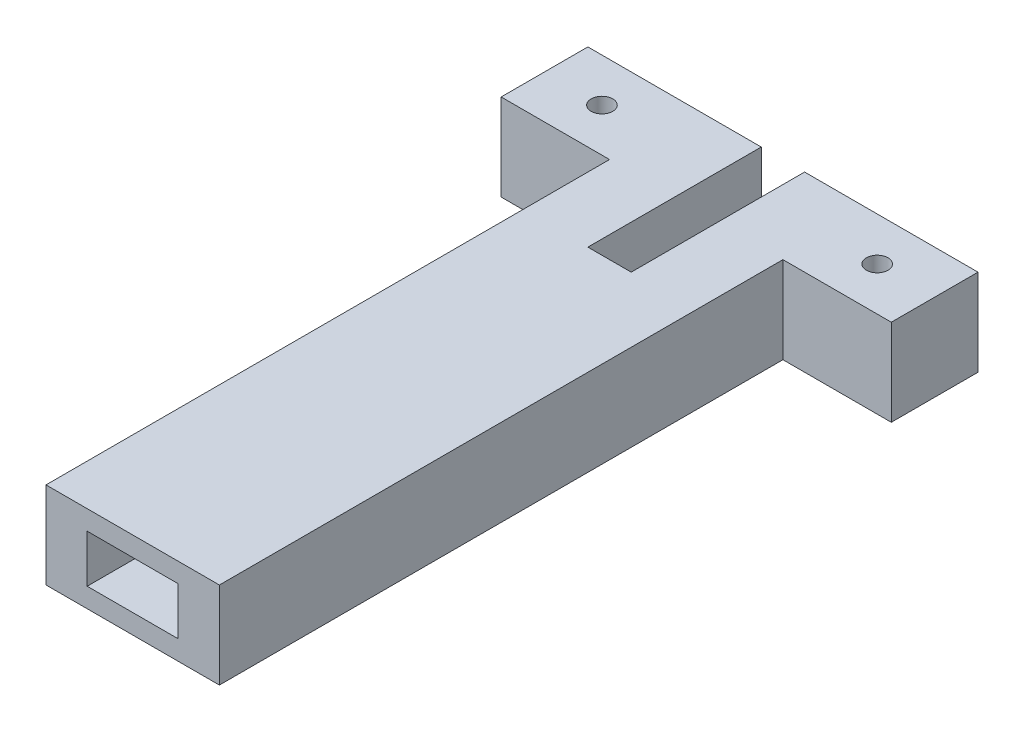
SolidWorks part; units mm, degrees
ref_plane "Front Plane" through (0, 0, 0) normal (0, 0, 1) x (1, 0, 0)
ref_plane "Top Plane" through (0, 0, 0) normal (0, 1, 0) x (1, 0, 0)
ref_plane "Right Plane" through (0, 0, 0) normal (1, 0, 0) x (0, 0, -1)
sketch "Sketch1" plane through (0, 0, 0) normal (0, 1, 0) x (1, 0, 0)
  line L0 (10, -5) -> (22.5, -5)
  line L1 (-22.5, -5) -> (-10, -5)
  line L2 (-22.5, -5) -> (-22.5, 5)
  line L3 (-22.5, 5) -> (-2.5, 5)
  line L4 (22.5, -5) -> (22.5, 5)
  line L5 (-22.5, -5) -> (22.5, 5) construction
  line L6 (-22.5, 5) -> (22.5, -5) construction
  line L7 (-10, -70) -> (10, -70)
  line L8 (-10, -70) -> (-10, -5)
  line L10 (10, -70) -> (10, -5)
  line L11 (-10, -70) -> (10, -5) construction
  line L12 (-10, -5) -> (10, -70) construction
  line L13 (2.5, 5) -> (22.5, 5)
  line L14 (-2.5, -15) -> (2.5, -15)
  line L15 (-2.5, -15) -> (-2.5, 5)
  line L17 (2.5, -15) -> (2.5, 5)
  line L18 (-2.5, -15) -> (2.5, 5) construction
  line L19 (-2.5, 5) -> (2.5, -15) construction
  circle A0 centre (-15.875, 0) radius 1.25
  circle A1 centre (15.875, 0) radius 1.25
  point P0 (0, 0)
  point P10 (0, -37.5)
  point P15 (0, -15)
  point P17 (0, -5)
  dimension "D2" = 15.875
  dimension "D3" = 31.75
  dimension "D4" = 2.5
  dimension "D5" = 2.5
  dimension "D1" = 45
  dimension "D6" = 65
  dimension "D7" = 20
  dimension "D8" = 10
  dimension "D9" = 5
  dimension "D10" = 20
extrude "Boss-Extrude1" add sketch "Sketch1" along normal blind 10
sketch "Sketch2" plane through (0, 0, 70) normal (0, 0, 1) x (1, 0, 0)
  line L0 (22.5, 10) -> (22.5, 0) construction
  line L1 (-5.25, 2.25) -> (5.25, 2.25)
  line L2 (-5.25, 2.25) -> (-5.25, 7.75)
  line L3 (-5.25, 7.75) -> (5.25, 7.75)
  line L4 (5.25, 2.25) -> (5.25, 7.75)
  line L5 (-5.25, 2.25) -> (5.25, 7.75) construction
  line L6 (-5.25, 7.75) -> (5.25, 2.25) construction
  point P0 (0, 5)
  point P5 (0, 0)
  point P7 (0, 0)
  point P10 (22.5, 5)
  dimension "D1" = 5.5
  dimension "D2" = 10.5
extrude "Cut-Extrude1" cut sketch "Sketch2" against normal up to surface (55 mm away) up to face at (0, 5, 15)
